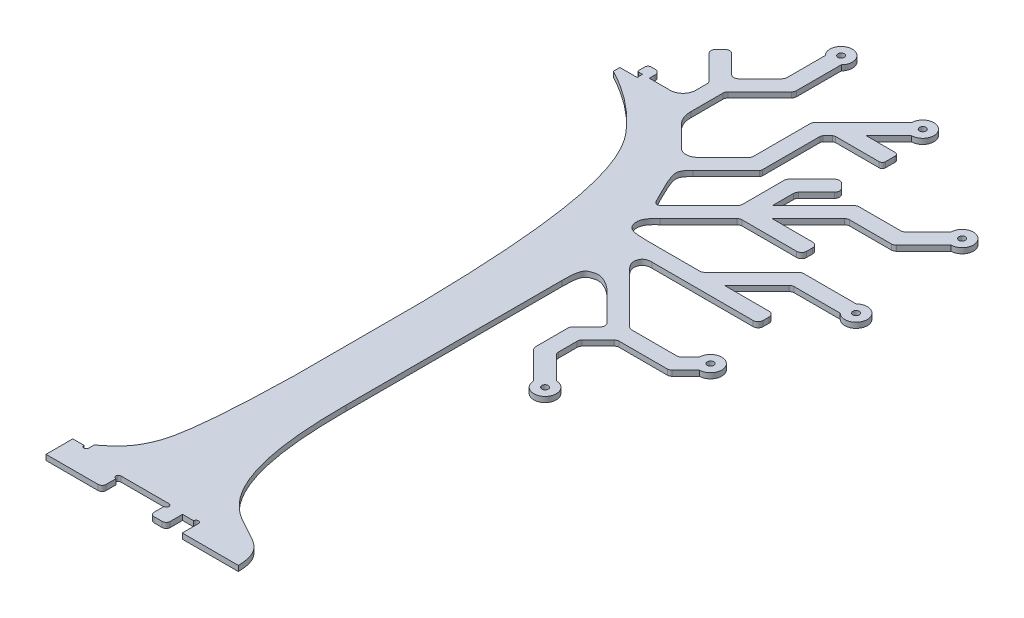
SolidWorks part; units mm, degrees
material "Balsa"
ref_plane "Front Plane" through (0, 0, 0) normal (0, 0, 1) x (1, 0, 0)
ref_plane "Top Plane" through (0, 0, 0) normal (0, 1, 0) x (1, 0, 0)
ref_plane "Right Plane" through (0, 0, 0) normal (1, 0, 0) x (0, 0, -1)
sketch "Sketch1" plane through (0, 0, 0) normal (0, 1, 0) x (1, 0, 0)
  line L0 (0, 33.4) -> (0, 40.1)
  line L1 (0, 40.1) -> (0, 33.4)
  line L2 (50, 5) -> (50, 17.3)
  line L3 (0, 0) -> (45, 0)
  line L4 (50, 23.4) -> (110, 23.4)
  line L5 (110, 17.3) -> (110, 5)
  line L6 (115, 0) -> (125, 0)
  line L7 (114, 240) -> (114, 510)
  line L8 (-80, 768) -> (-80, 776)
  line L9 (-50, 790.1) -> (-50, 782.7)
  line L10 (65.4558, 727.2442) -> (98.2254, 760.0137)
  line L11 (-50, 782.7) -> (-40, 782.7)
  line L12 (-63, 782.7) -> (-58.475, 782.7)
  line L13 (50, 400) -> (50, 240)
  line L14 (154, 526) -> (187.9411, 492.0589)
  line L15 (187.9411, 483.2908) -> (170.9706, 466.3202)
  line L16 (178.3622, 707.6362) -> (228.9304, 707.6362)
  line L17 (304.3852, 804.8071) -> (318.5273, 790.665) construction
  line L18 (169.1546, 461.9361) -> (169.1546, 421.9361)
  line L19 (170.9706, 417.5521) -> (204.9117, 383.6109)
  line L20 (282.7473, 599.537) -> (282.7473, 591.937)
  line L21 (219.0538, 397.7531) -> (190.9706, 425.8363)
  line L22 (189.1546, 430.2204) -> (189.1546, 453.6519)
  line L23 (190.9706, 458.0359) -> (210.9357, 478.001)
  line L24 (215.3197, 479.8169) -> (275.3197, 479.8169)
  line L25 (279.7038, 481.6329) -> (296.6743, 498.6034)
  line L26 (-56, 796.1) -> (-61, 796.1)
  line L27 (282.5322, 512.7456) -> (271.4195, 501.6329)
  line L28 (267.0354, 499.8169) -> (211.0354, 499.8169)
  line L29 (206.6514, 501.6329) -> (146.5473, 561.737)
  line L30 (235.1304, 701.4362) -> (235.1304, 693.8362)
  line L31 (228.9304, 687.6362) -> (160.9304, 687.6362)
  line L32 (156.5463, 685.8202) -> (108.463, 637.737)
  line L33 (219.0538, 397.7531) -> (204.9117, 383.6109) construction
  line L34 (282.5322, 512.7456) -> (296.6743, 498.6034) construction
  line L35 (150.5473, 585.737) -> (276.5473, 585.737)
  line L36 (-58.475, 782.7) -> (-58.475, 776)
  line L37 (99.397, 762.8421) -> (99.397, 834.5284)
  line L38 (100.5685, 837.3569) -> (161.6224, 898.4107)
  line L39 (276.5473, 605.737) -> (220.7473, 605.737)
  line L40 (220.7473, 605.737) -> (261.1568, 646.1464)
  line L41 (-8, 798.7) -> (-8, 812.7)
  line L42 (-9.8159, 817.0841) -> (-39.5144, 846.7825)
  line L43 (-39.5144, 855.5507) -> (-34.1404, 860.9247)
  line L44 (-25.3723, 860.9247) -> (-2.3841, 837.9365)
  line L45 (6.3841, 837.9365) -> (33.4139, 864.9663)
  line L46 (35.2299, 869.3504) -> (35.2299, 917.0661)
  line L47 (265.5408, 647.9624) -> (322.9727, 647.9624)
  line L48 (55.2299, 917.0661) -> (55.2299, 861.0661)
  line L49 (53.4139, 856.682) -> (13.8159, 817.0841)
  line L50 (12, 812.7) -> (12, 772.7)
  line L51 (96.6432, 654.2014) -> (142.6052, 700.1634)
  line L52 (144.4211, 704.5474) -> (144.4211, 756.5474)
  line L53 (146.237, 760.9315) -> (174.5213, 789.2158)
  line L54 (183.2894, 789.2158) -> (188.6635, 783.8418)
  line L55 (188.6635, 775.0736) -> (166.237, 752.6472)
  line L56 (164.4211, 748.2632) -> (164.4211, 721.9793)
  line L57 (164.4211, 721.9793) -> (215.3328, 772.891)
  line L58 (219.7169, 774.7069) -> (271.7169, 774.7069)
  line L59 (276.1009, 776.5229) -> (304.3852, 804.8071)
  line L60 (45.4558, 727.2442) -> (20, 752.7)
  line L61 (318.5273, 790.665) -> (284.3852, 756.5229)
  line L62 (280.0011, 754.7069) -> (228.0011, 754.7069)
  line L63 (223.6171, 752.891) -> (178.3622, 707.6362)
  line L64 (322.9727, 667.9624) -> (257.2566, 667.9624)
  line L65 (252.8725, 666.1464) -> (194.279, 607.5529)
  line L66 (189.8949, 605.737) -> (124.463, 605.737)
  line L67 (175.7645, 884.2685) -> (147.4802, 855.9843)
  line L68 (147.4802, 855.9843) -> (183.4802, 855.9843)
  line L69 (187.4802, 851.9843) -> (187.4802, 839.9843)
  line L70 (183.4802, 835.9843) -> (129.1371, 835.9843)
  line L71 (126.3087, 834.8127) -> (120.5685, 829.0726)
  line L72 (119.397, 826.2442) -> (119.397, 754.5579)
  line L73 (118.2254, 751.7294) -> (76.9706, 710.4746)
  line L74 (161.6224, 898.4107) -> (175.7645, 884.2685) construction
  line L75 (-40, 782.7) -> (-24, 782.7)
  line L76 (-80, 776) -> (-65, 776)
  line L77 (-65, 784.7) -> (-65, 792.1)
  line L78 (-58.475, 776) -> (-65, 776)
  line L79 (130, 5) -> (130, 20.35)
  line L80 (130, 20.35) -> (143.9, 20.35)
  line L81 (150, 20.35) -> (150, 0)
  line L82 (150, 0) -> (220, 0)
  line L83 (-6.1, 33.4) -> (-20, 33.4)
  line L84 (-20, 33.4) -> (-20, 0)
  line L85 (-20, 0) -> (0, 0)
  arc A0 (296.6743, 498.6034) -> (282.5322, 512.7456) centre (296.5315, 512.6027) ccw
  circle A1 centre (296.5315, 512.6027) radius 4
  arc A2 (204.9117, 383.6109) -> (219.0538, 397.7531) centre (218.911, 383.7538) ccw
  circle A3 centre (218.911, 383.7538) radius 4
  arc A4 (318.5273, 790.665) -> (304.3852, 804.8071) centre (318.3845, 804.6643) ccw
  circle A5 centre (318.3845, 804.6643) radius 4
  arc A6 (55.2299, 917.0661) -> (35.2299, 917.0661) centre (45.2299, 926.8641) ccw
  circle A7 centre (45.2299, 926.8641) radius 4
  arc A8 (53.4139, 856.682) -> (55.2299, 861.0661) centre (49.0299, 861.0661) ccw
  arc A9 (33.4139, 864.9663) -> (35.2299, 869.3504) centre (29.0299, 869.3504) ccw
  arc A10 (6.3841, 837.9365) -> (-2.3841, 837.9365) centre (2, 842.3205) cw
  arc A11 (-25.3723, 860.9247) -> (-34.1404, 860.9247) centre (-29.7563, 856.5406) ccw
  arc A12 (-39.5144, 846.7825) -> (-39.5144, 855.5507) centre (-35.1304, 851.1666) cw
  arc A13 (12, 812.7) -> (13.8159, 817.0841) centre (18.2, 812.7) cw
  arc A14 (-9.8159, 817.0841) -> (-8, 812.7) centre (-14.2, 812.7) cw
  arc A15 (170.9706, 417.5521) -> (169.1546, 421.9361) centre (175.3546, 421.9361) cw
  arc A16 (190.9706, 425.8363) -> (189.1546, 430.2204) centre (195.3546, 430.2204) cw
  arc A17 (169.1546, 461.9361) -> (170.9706, 466.3202) centre (175.3546, 461.9361) cw
  arc A18 (189.1546, 453.6519) -> (190.9706, 458.0359) centre (195.3546, 453.6519) cw
  arc A19 (210.9357, 478.001) -> (215.3197, 479.8169) centre (215.3197, 473.6169) cw
  arc A20 (279.7038, 481.6329) -> (275.3197, 479.8169) centre (275.3197, 486.0169) cw
  arc A21 (187.9411, 483.2908) -> (187.9411, 492.0589) centre (183.5571, 487.6748) ccw
  arc A22 (206.6514, 501.6329) -> (211.0354, 499.8169) centre (211.0354, 506.0169) ccw
  arc A23 (271.4195, 501.6329) -> (267.0354, 499.8169) centre (267.0354, 506.0169) cw
  arc A24 (160.9304, 687.6362) -> (156.5463, 685.8202) centre (160.9304, 681.4362) ccw
  arc A25 (144.4211, 704.5474) -> (142.6052, 700.1634) centre (138.2211, 704.5474) cw
  arc A26 (144.4211, 756.5474) -> (146.237, 760.9315) centre (150.6211, 756.5474) cw
  arc A27 (174.5213, 789.2158) -> (183.2894, 789.2158) centre (178.9054, 784.8317) cw
  arc A28 (188.6635, 783.8418) -> (188.6635, 775.0736) centre (184.2794, 779.4577) cw
  arc A29 (166.237, 752.6472) -> (164.4211, 748.2632) centre (170.6211, 748.2632) ccw
  arc A30 (223.6171, 752.891) -> (228.0011, 754.7069) centre (228.0011, 748.5069) cw
  arc A31 (276.1009, 776.5229) -> (271.7169, 774.7069) centre (271.7169, 780.9069) cw
  arc A32 (215.3328, 772.891) -> (219.7169, 774.7069) centre (219.7169, 768.5069) cw
  arc A33 (284.3852, 756.5229) -> (280.0011, 754.7069) centre (280.0011, 760.9069) cw
  arc A34 (235.1304, 701.4362) -> (228.9304, 707.6362) centre (228.9304, 701.4362) ccw
  arc A35 (235.1304, 693.8362) -> (228.9304, 687.6362) centre (228.9304, 693.8362) cw
  arc A36 (322.9727, 647.9624) -> (322.9727, 667.9624) centre (332.7707, 657.9624) ccw
  circle A37 centre (332.7707, 657.9624) radius 4
  arc A38 (276.5473, 585.737) -> (282.7473, 591.937) centre (276.5473, 591.937) ccw
  arc A39 (282.7473, 599.537) -> (276.5473, 605.737) centre (276.5473, 599.537) ccw
  arc A40 (261.1568, 646.1464) -> (265.5408, 647.9624) centre (265.5408, 641.7624) cw
  arc A41 (257.2566, 667.9624) -> (252.8725, 666.1464) centre (257.2566, 661.7624) ccw
  arc A42 (194.279, 607.5529) -> (189.8949, 605.737) centre (189.8949, 611.937) cw
  arc A43 (-50, 790.1) -> (-56, 796.1) centre (-56, 790.1) ccw
  arc A44 (-63, 782.7) -> (-65, 784.7) centre (-63, 784.7) cw
  arc A45 (175.7645, 884.2685) -> (161.6224, 898.4107) centre (175.6216, 898.2678) ccw
  circle A46 centre (175.6216, 898.2678) radius 4
  arc A47 (20, 752.7) -> (12, 772.7) centre (39.3333, 772.0333) cw
  arc A48 (45.4558, 727.2442) -> (65.4558, 727.2442) centre (55.4558, 737.2442) ccw
  arc A49 (99.397, 834.5284) -> (100.5685, 837.3569) centre (103.397, 834.5284) cw
  arc A50 (98.2254, 760.0137) -> (99.397, 762.8421) centre (95.397, 762.8421) ccw
  arc A51 (119.397, 754.5579) -> (118.2254, 751.7294) centre (115.397, 754.5579) cw
  arc A52 (120.5685, 829.0726) -> (119.397, 826.2442) centre (123.397, 826.2442) ccw
  arc A53 (129.1371, 835.9843) -> (126.3087, 834.8127) centre (129.1371, 831.9843) ccw
  arc A54 (187.4802, 839.9843) -> (183.4802, 835.9843) centre (183.4802, 839.9843) cw
  arc A55 (183.4802, 855.9843) -> (187.4802, 851.9843) centre (183.4802, 851.9843) cw
  arc A56 (110, 5) -> (115, 0) centre (115, 5) ccw
  arc A57 (50, 5) -> (45, 0) centre (45, 5) cw
  arc A58 (-61, 796.1) -> (-65, 792.1) centre (-61, 792.1) ccw
  arc A59 (-24, 782.7) -> (-8, 798.7) centre (-24, 798.7) ccw
  arc A60 (130, 5) -> (125, 0) centre (125, 5) cw
  arc A61 (150, 20.35) -> (143.9, 20.35) centre (146.95, 20.35) ccw
  arc A62 (0, 33.4) -> (-6.1, 33.4) centre (-3.05, 33.4) cw
  arc A63 (110, 23.4) -> (110, 17.3) centre (110, 20.35) cw
  arc A64 (50, 23.4) -> (50, 17.3) centre (50, 20.35) ccw
  spline S0 degree 3 poles (220, 0) (219.8909, 29.6594) (199.1827, 36.8183) (129.4342, 76.0787) (113.7419, 150.6034) (114, 240) knots 0 0 0 0 0.323232 0.423232 1 1 1 1
  spline S1 degree 3 poles (0, 40.1) (19.1957, 54.4268) (27.8767, 66.5443) (42.0204, 101.0239) (48.2138, 152.2481) (50, 240) knots 0 0 0 0 0.453257 0.553257 1 1 1 1
  spline S2 degree 3 poles (50, 400) (47.6585, 541.154) (33.1961, 666.5435) (-32.2473, 739.1951) (-56.4465, 755.1122) (-80, 768) knots 0 0 0 0 0.547343 0.647343 1 1 1 1
  spline S3 degree 3 poles (114, 510) (113.5516, 535.6335) (120.8954, 535.8014) (132.1447, 540.677) (144.8483, 535.1096) (154, 526) knots 0 0 0 0 0.414773 0.514773 1 1 1 1
  spline S4 degree 3 poles (76.9706, 710.4746) (66.7466, 700.3328) (66.0673, 696.6305) (89.0134, 650.1039) (89.6806, 647.9666) (96.6432, 654.2014) knots 0 0 0 0 0.497958 0.597958 1 1 1 1
  spline S5 degree 3 poles (146.5473, 561.737) (141.633, 565.9431) (137.2605, 571.4849) (139.6653, 583.5673) (144.9166, 585.8456) (150.5473, 585.737) knots 0 0 0 0 0.464052 0.564052 1 1 1 1
  spline S6 degree 3 poles (124.463, 605.737) (105.3793, 605.7158) (100.6837, 608.3023) (94.629, 623.12) (100.4051, 630.9459) (108.463, 637.737) knots 0 0 0 0 0.366768 0.366768 1 1 1 1
  point P49 (205.0122, 411.7947)
  point P79 (177.4503, 763.8604)
  point P148 (282.7473, 585.737)
  point P152 (282.7473, 605.737)
  point P155 (262.9727, 647.9624)
  point P158 (254.6884, 667.9624)
  point P161 (192.463, 605.737)
  point P162 (-50, 796.1)
  point P165 (-65, 788.4)
  point P170 (119.397, 790.401)
  point P189 (99.397, 836.1853)
  point P192 (99.397, 761.1853)
  point P195 (119.397, 752.901)
  point P204 (187.4802, 855.9843)
  point P209 (110, 0)
  point P212 (50, 0)
  point P215 (-65, 782.7)
  point P218 (-8, 782.7)
  point P227 (130, 0)
  point P235 (0, 0)
  dimension "D30" = 8
  dimension "D34" = 8
  dimension "D35" = 8
  dimension "D36" = 8
  dimension "D37" = 6.2
  dimension "D38" = 14
  dimension "D39" = 14
  dimension "D40" = 14
  dimension "D41" = 14
  dimension "D79" = 8
  dimension "D80" = 14
  dimension "D81" = 6.2
  dimension "D102" = 6
  dimension "D104" = 8
  dimension "D105" = 14
  dimension "D119" = 4
  dimension "D122" = 5
  dimension "D121" = 16
  dimension "D127" = 2
  dimension "D128" = 4
  dimension "D131" = 5
  dimension "D135" = 3.05
  dimension "D136" = 3.05
  dimension "D138" = 3.05
  dimension "D1" = 23.4
  dimension "D2" = 220
  dimension "D3" = 60
  dimension "D4" = 50
  dimension "D8" = 10
  dimension "D9" = 8
  dimension "D10" = 240
  dimension "D11" = 64
  dimension "D12" = 240
  dimension "D16" = 20
  dimension "D17" = 20
  dimension "D18" = 20
  dimension "D19" = 20
  dimension "D20" = 20
  dimension "D21" = 20
  dimension "D22" = 20
  dimension "D23" = 20
  dimension "D24" = 20
  dimension "D25" = 20
  dimension "D26" = 20
  dimension "D27" = 20
  dimension "D28" = 20
  dimension "D29" = 20
  dimension "D15" = 20
  dimension "D33" = 20
  dimension "D5" = 30
  dimension "D13" = 42
  dimension "D14" = 56
  dimension "D31" = 56
  dimension "D43" = 135
  dimension "D44" = 45
  dimension "D45" = 72
  dimension "D46" = 52
  dimension "D47" = 40
  dimension "D49" = 52
  dimension "D50" = 40
  dimension "D51" = 68
  dimension "D52" = 64
  dimension "D53" = 135
  dimension "D54" = 48
  dimension "D55" = 24
  dimension "D56" = 40
  dimension "D57" = 48
  dimension "D58" = 60
  dimension "D59" = 24
  dimension "D60" = 56
  dimension "D63" = 40
  dimension "D66" = 80
  dimension "D69" = 20
  dimension "D71" = 20
  dimension "D72" = 20
  dimension "D73" = 135
  dimension "D48" = 65
  dimension "D76" = 68
  dimension "D77" = 40
  dimension "D64" = 16
  dimension "D65" = 270
  dimension "D68" = 68
  dimension "D78" = 60
  dimension "D70" = 62
  dimension "D75" = 88
  dimension "D82" = 85
  dimension "D83" = 126
  dimension "D84" = 44
  dimension "D85" = 50
  dimension "D86" = 35
  dimension "D87" = 44
  dimension "D88" = 72
  dimension "D89" = 56
  dimension "D92" = 10
  dimension "D93" = 24
  dimension "D94" = 12
  dimension "D95" = 8
  dimension "D96" = 12
  dimension "D97" = 28
  dimension "D98" = 160
  dimension "D67" = 24
  dimension "D74" = 4
  dimension "D61" = 32
  dimension "D62" = 16
  dimension "D106" = 20
  dimension "D107" = 20
  dimension "D108" = 20
  dimension "D109" = 135
  dimension "D110" = 20
  dimension "D111" = 48
  dimension "D112" = 75
  dimension "D113" = 88
  dimension "D114" = 40
  dimension "D90" = 20
  dimension "D91" = 8
  dimension "D115" = 20
  dimension "D116" = 36
  dimension "D117" = 60
  dimension "D118" = 40
  dimension "D42" = 40.1
  dimension "D123" = 40
  dimension "D124" = 2
  dimension "D125" = 15
  dimension "D100" = 15
  dimension "D32" = 776
  dimension "D103" = 13.4
  dimension "D101" = 32
  dimension "D99" = 6.7
  dimension "D120" = 6.525
  dimension "D126" = 15
  dimension "D129" = 20
  dimension "D130" = 20.35
  dimension "D132" = 20
  dimension "D133" = 20
  dimension "D134" = 6.7
  dimension "D137" = 20
  dimension "D139" = 23.4
extrude "Boss-Extrude1" add sketch "Sketch1" along normal blind 6.7
equation "\"BranchWidth\"= 20mm"
equation "\"StockThickness\"= 6.7mm"
equation "\"D16@Sketch1\"= \"BranchWidth\""
equation "\"D1@Sketch1\" = \"Base thickness\""
equation "\"D17@Sketch1\"= \"BranchWidth\""
equation "\"D18@Sketch1\"= \"BranchWidth\""
equation "\"D19@Sketch1\"= \"BranchWidth\""
equation "\"D20@Sketch1\"= \"BranchWidth\""
equation "\"D21@Sketch1\"= \"BranchWidth\""
equation "\"D22@Sketch1\"= \"BranchWidth\""
equation "\"D23@Sketch1\"= \"BranchWidth\""
equation "\"D24@Sketch1\"= \"BranchWidth\""
equation "\"D25@Sketch1\"= \"BranchWidth\""
equation "\"D26@Sketch1\"= \"BranchWidth\""
equation "\"D27@Sketch1\"= \"BranchWidth\""
equation "\"D28@Sketch1\"= \"BranchWidth\""
equation "\"D29@Sketch1\"= \"BranchWidth\""
equation "\"D15@Sketch1\"= \"BranchWidth\""
equation "\"LeafHoleDiameter\"= 8mm"
equation "\"D30@Sketch1\"= \"LeafHoleDiameter\""
equation "\"D34@Sketch1\"= \"LeafHoleDiameter\""
equation "\"D35@Sketch1\"= \"LeafHoleDiameter\""
equation "\"D36@Sketch1\"= \"LeafHoleDiameter\""
equation "\"D33@Sketch1\"=\"BranchWidth\""
equation "\"LeafRadius\"= 14mm"
equation "\"D38@Sketch1\"= \"LeafRadius\""
equation "\"D39@Sketch1\"= \"LeafRadius\""
equation "\"D40@Sketch1\"= \"LeafRadius\""
equation "\"D41@Sketch1\"= \"LeafRadius\""
equation "\"D1@Boss-Extrude1\"=\"StockThickness\""
equation "\"D69@Sketch1\"=\"BranchWidth\""
equation "\"D71@Sketch1\"=\"BranchWidth\""
equation "\"D72@Sketch1\"=\"BranchWidth\""
equation "\"D80@Sketch1\"=\"LeafRadius\""
equation "\"D79@Sketch1\"=\"LeafHoleDiameter\""
equation "\"D106@Sketch1\"=\"BranchWidth\""
equation "\"D105@Sketch1\"=\"LeafRadius\""
equation "\"D104@Sketch1\"=\"LeafHoleDiameter\""
equation "\"D107@Sketch1\"=\"BranchWidth\""
equation "\"D108@Sketch1\"=\"BranchWidth\""
equation "\"D110@Sketch1\"=\"BranchWidth\""
equation "\"D42@Sketch1\"= \"Base thickness\" + \"StockThickness\" + 10"
equation "\"Dogbone radius\"= 3.05mm"
equation "\"Foot\"= 60 - \"Dogbone radius\""
equation "\"FootBridge\"= 60 + 2 * \"Dogbone radius\""
equation "\"D103@Sketch1\"=\"StockThickness\" * 2"
equation "\"D99@Sketch1\"=\"StockThickness\""
equation "\"Base thickness\"= \"StockThickness\" * 2 - \"Base Tabs pocket depth\" * 2 + \"Base Tabs thickness\""
equation "\"D130@Sketch1\"=\"Base thickness\" - \"Dogbone radius\""
equation "\"D134@Sketch1\"= \"StockThickness\""
equation "\"Base Tabs thickness\"= 12"
equation "\"Base Tabs pocket depth\"= 1"
equation "\"D120@Sketch1\"= 5+ \"Dogbone radius\" / 2"
equation "\"D135@Sketch1\"=\"Dogbone radius\""
equation "\"D136@Sketch1\"=\"Dogbone radius\""
equation "\"D138@Sketch1\"= \"Dogbone radius\""
equation "\"D139@Sketch1\"= \"Base thickness\""
